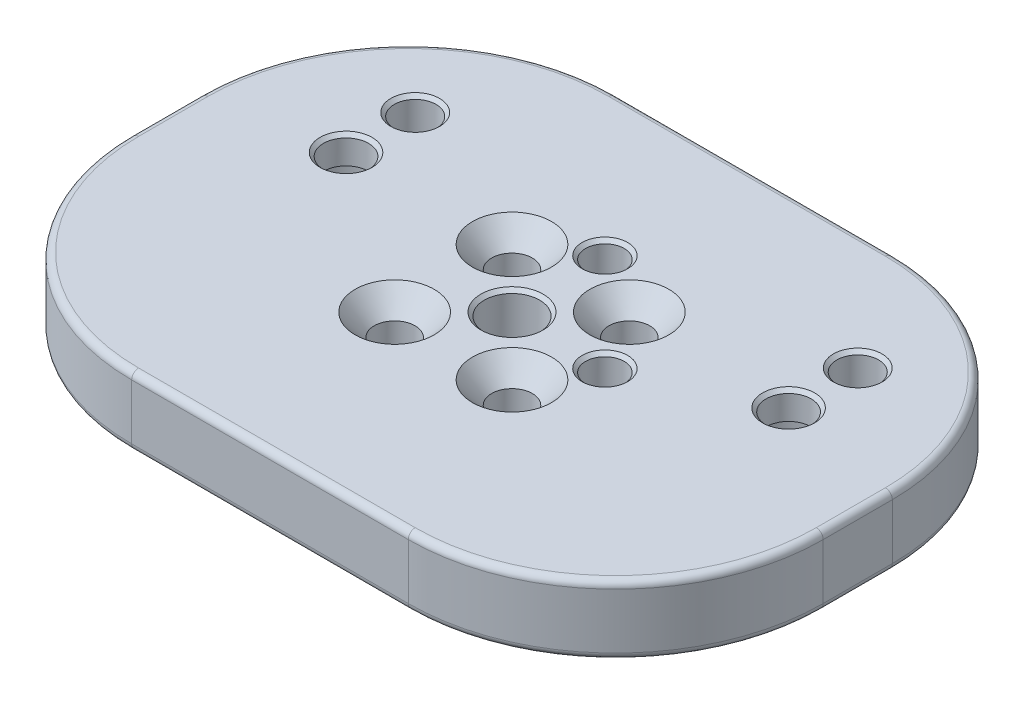
SolidWorks part; units mm, degrees
ref_plane "Front Plane" through (0, 0, 0) normal (0, 0, 1) x (1, 0, 0)
ref_plane "Top Plane" through (0, 0, 0) normal (0, 1, 0) x (1, 0, 0)
ref_plane "Right Plane" through (0, 0, 0) normal (1, 0, 0) x (0, 0, -1)
sketch "Sketch1" plane through (0, 0, 0) normal (0, 1, 0) x (1, 0, 0)
  line L1 (-25, 17.5) -> (25, 17.5)
  line L2 (-25, 17.5) -> (-25, -17.5)
  line L3 (-25, -17.5) -> (25, -17.5)
  line L4 (25, 17.5) -> (25, -17.5)
  line L5 (-25, 17.5) -> (25, -17.5) construction
  line L6 (-25, -17.5) -> (25, 17.5) construction
  point P0 (0, 0)
  dimension "D1" = 50
  dimension "D2" = 35
extrude "Boss-Extrude2" add sketch "Sketch1" against normal blind 5
sketch "Sketch2" plane through (0, 0, 0) normal (0, 1, 0) x (1, 0, 0)
  circle A0 centre (0, 0) radius 2
  dimension "D1" = 4
extrude "Cut-Extrude1" cut sketch "Sketch2" against normal through all
sketch "Sketch3" plane through (0, -5, 0) normal (0, -1, 0) x (1, 0, 0)
  circle A0 centre (0, 0) radius 9
  dimension "D1" = 18
extrude "Cut-Extrude2" cut sketch "Sketch3" against normal blind 1.5
sketch "Sketch4" plane through (0, -3.5, 0) normal (0, -1, 0) x (1, 0, 0)
  line L0 (-9, 0) -> (9, 0) construction
  line L1 (-4.2426, -4.2426) -> (4.2426, -4.2426) construction
  line L2 (-4.2426, 4.2426) -> (4.0605, 4.2426) construction
  line L3 (0, 0) -> (-4.2426, -4.2426) construction
  line L4 (-4.2426, -4.2426) -> (4.2426, -4.2426) construction
  line L5 (4.2426, -4.2426) -> (0, 0) construction
  line L6 (-4.2426, 4.2426) -> (0, 0) construction
  line L7 (0, 0) -> (4.2426, 4.2426) construction
  line L8 (4.2426, 4.2426) -> (-4.2426, 4.2426) construction
  circle A0 centre (-4.2426, 4.2426) radius 0.8
  circle A1 centre (4.2426, 4.2426) radius 0.8
  circle A2 centre (-4.2426, -4.2426) radius 0.8
  circle A3 centre (4.2426, -4.2426) radius 0.8
  circle A4 centre (0, 0) radius 9 construction
  point P8 (0, 0)
  dimension "D1" = 1.6
  dimension "D2" = 6
  dimension "D3" = 6
  dimension "D4" = 6
  dimension "D5" = 6
  dimension "D6" = 45
  dimension "D7" = 45
  dimension "D8" = 45
  dimension "D9" = 45
sketch "Sketch5" plane through (0, -3.5, 0) normal (0, -1, 0) x (1, 0, 0)
  circle A0 centre (0, 0) radius 3.1769
sketch "Sketch6" plane through (0, 0, 0) normal (0, 1, 0) x (1, 0, 0)
  circle A0 centre (-16, 9) radius 1.5113
  circle A1 centre (16, 9) radius 1.5113
  dimension "D3" = 3.0226
  dimension "D1" = 9
  dimension "D2" = 16
  dimension "D4" = 32
extrude "Cut-Extrude5" cut sketch "Sketch6" against normal blind 4.8
sketch "Sketch7" plane through (0, 0, 0) normal (0, 1, 0) x (1, 0, 0)
  circle A0 centre (-16, 4) radius 1.632
  circle A1 centre (16, 4) radius 1.632
  dimension "D3" = 3.2639
  dimension "D1" = 16
  dimension "D2" = 4
  dimension "D4" = 32
extrude "Cut-Extrude6" cut sketch "Sketch7" against normal through all
sketch "Sketch8" plane through (0, -3.5, 0) normal (0, -1, 0) x (1, 0, 0)
  circle A0 centre (-6, 0) radius 1.95
  dimension "D1" = 3.9
  dimension "D2" = 6
extrude "Boss-Extrude3" add sketch "Sketch8" along normal blind 2
fillet "Fillet1" radius 15 4 edges at (-25, -2.5, -17.5) (25, -2.5, -17.5) (25, -2.5, 17.5) (-25, -2.5, 17.5)
sketch "Sketch10" plane through (0, -5, 0) normal (0, -1, 0) x (1, 0, 0)
  circle A0 centre (-16, -4) radius 2.8575
  circle A1 centre (16, -4) radius 2.8575
extrude "Cut-Extrude9" cut sketch "Sketch10" against normal blind 3
sketch "Sketch19" plane through (0, 0, 0) normal (0, 1, 0) x (1, 0, 0)
  circle A0 centre (4.2426, 4.2426) radius 0.8
  circle A1 centre (-4.2426, 4.2426) radius 0.8
  circle A2 centre (-4.2426, -4.2426) radius 0.8
  circle A3 centre (4.2426, -4.2426) radius 0.8
  dimension "D1" = 1.6
hole_wizard "CSK for #4 Flat Head Machine Screw1" positions "3DSketch3" profile "Sketch22" countersink size "#4" standard "ANSI Inch" end condition through all
sketch3d "3DSketch3"
  point P0 (4.2426, 0, -4.2426)
  point P3 (4.2426, 0, 4.2426)
  point P6 (-4.2426, 0, 4.2426)
  point P9 (-4.2426, 0, -4.2426)
sketch "Sketch22" plane through (4.2426, 0, -4.2426) normal (1, 0, 0) x (0, 0, 1)
  line L0 (0, 0) -> (0, 5.5)
  line L1 (0, 5.5) -> (1.4732, 5.5)
  line L2 (1.4732, 5.5) -> (1.4732, 1.5925)
  line L3 (1.4732, 1.5925) -> (2.8575, 0)
  line L5 (2.8575, 0) -> (0, 0)
  line L6 (-1.4732, 1.5925) -> (-2.8575, 0) construction
  line L11 (0, -6.35) -> (0, 107.95) construction
  dimension "Thru Hole Dia." = 2.9464
  dimension "Thru Hole Depth" = 5.5
  dimension "Near C'Sink Dia." = 5.715
  dimension "Near C'Sink Angle" = 82
sketch "Sketch23" plane through (0, 0, 0) normal (0, 1, 0) x (1, 0, 0)
  line L0 (-0.1768, 6.8943) -> (6.8943, -0.1768) construction
  line L1 (4.2426, 4.2426) -> (0, 0) construction
  circle A0 centre (-0.1768, 6.8943) radius 1.397
  circle A1 centre (6.8943, -0.1768) radius 1.397
  point P4 (3.3588, 3.3588)
  dimension "D2" = 2.794
  dimension "D1" = 10
  dimension "D3" = 4.75
extrude "Cut-Extrude13" cut sketch "Sketch23" against normal through all
sketch "Sketch24" plane through (0, -5, 0) normal (0, -1, 0) x (1, 0, 0)
  circle A0 centre (6.8943, 0.1768) radius 2.794
  circle A1 centre (-0.1768, -6.8943) radius 2.794
  dimension "D1" = 5.588
extrude "Cut-Extrude14" cut sketch "Sketch24" against normal blind 2.75
chamfer "Chamfer1" distance 0.25 angle 45 1 edges at (-6, -5.5, -1.95)
fillet "Fillet2" radius 0.5 16 edges at (-20.6066, -5, 13.1066) (-25, -5, 0) (-20.6066, -5, -13.1066) (0, -5, -17.5) (20.6066, -5, -13.1066) (25, -5, 0) (20.6066, -5, 13.1066) (-20.6066, 0, 13.1066) (-25, 0, 0) (-20.6066, 0, -13.1066) (0, 0, -17.5) (20.6066, 0, -13.1066) (25, 0, 0) (20.6066, 0, 13.1066) (0, -5, 17.5) (0, 0, 17.5)
chamfer "Chamfer2" distance 0.25 angle 45 7 edges at (16, 0, -7.4887) (16, 0, -2.368) (0, 0, 2) (6.8943, 0, 1.5738) (-0.1768, 0, -5.4973) (-16, 0, -2.368) (-16, 0, -7.4887)
